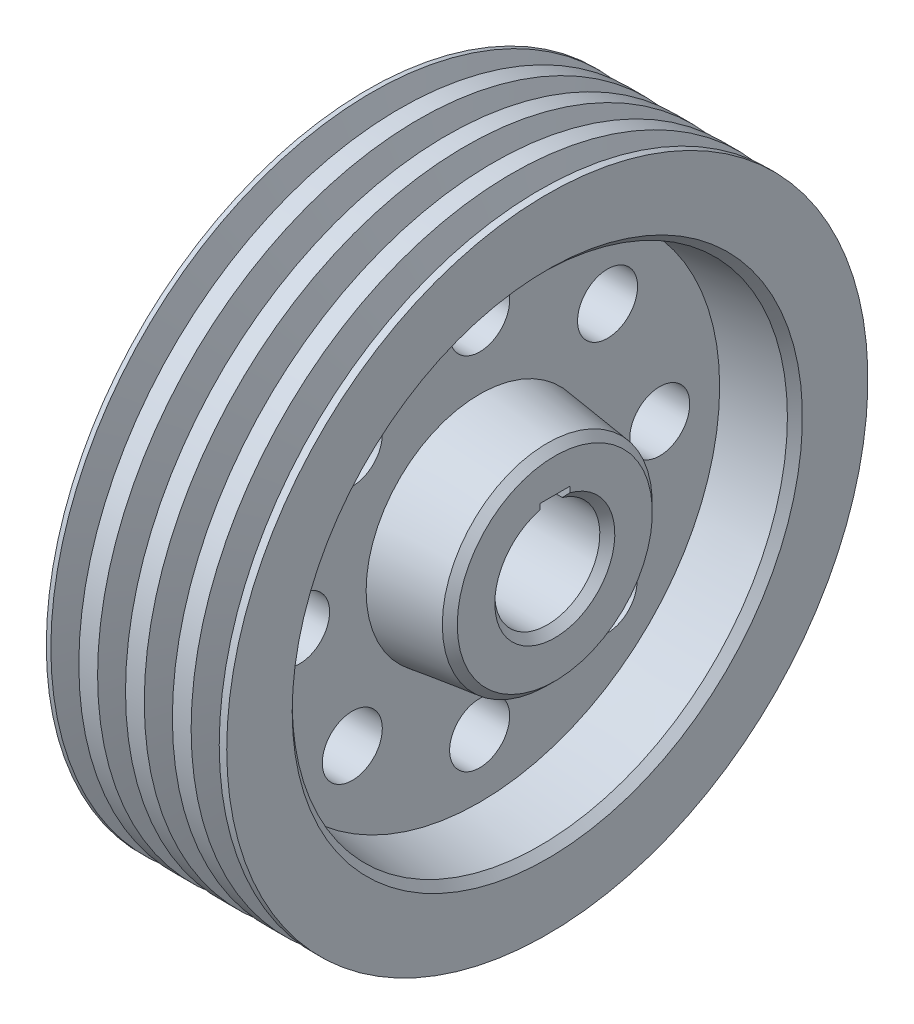
SolidWorks part; units mm, degrees
ref_plane "前视基准面" through (0, 0, 0) normal (0, 0, 1) x (1, 0, 0)
ref_plane "上视基准面" through (0, 0, 0) normal (0, 1, 0) x (1, 0, 0)
ref_plane "右视基准面" through (0, 0, 0) normal (1, 0, 0) x (0, 0, -1)
sketch "草图2" plane through (0, 0, 0) normal (0, 0, 1) x (1, 0, 0)
  line L0 (0, 0) -> (52, 0)
  line L3 (2, 14) -> (50, 14)
  line L4 (50, 68) -> (48, 66)
  line L5 (50, 27.9836) -> (31.9654, 30.2618)
  line L6 (52, 16) -> (52, 26)
  line L7 (0, 16) -> (2, 14)
  line L8 (50, 14) -> (52, 16)
  line L9 (5.9417, 77.6141) -> (3.2124, 85.5405)
  line L10 (2, 85.5405) -> (2, 68)
  line L11 (2, 85.5405) -> (3.2124, 85.5405)
  line L12 (52, 26) -> (50, 27.9836)
  line L14 (50, 68) -> (50, 85.45)
  line L15 (50, 85.45) -> (48, 85.45)
  line L16 (48, 85.45) -> (45.2863, 77.5688)
  line L17 (48, 66) -> (31.9654, 63.9744)
  line L18 (31.9654, 63.9744) -> (31.9654, 30.2618)
  line L19 (45.2863, 77.5688) -> (43.2863, 77.5688)
  line L20 (43.2863, 77.5688) -> (40.557, 85.4953)
  line L21 (40.557, 85.4953) -> (35.557, 85.4953)
  line L22 (35.557, 85.4953) -> (32.8433, 77.6141)
  line L23 (32.8433, 77.6141) -> (30.8433, 77.6141)
  line L24 (30.8433, 77.6141) -> (28.114, 85.5405)
  line L25 (28.114, 85.5405) -> (23.114, 85.5405)
  line L26 (23.114, 85.5405) -> (20.4003, 77.6594)
  line L27 (20.4003, 77.6594) -> (18.4003, 77.6141)
  line L28 (18.4003, 77.6141) -> (15.671, 85.5405)
  line L29 (15.671, 85.5405) -> (10.671, 85.5405)
  line L30 (10.671, 85.5405) -> (7.9417, 77.6141)
  line L31 (7.9417, 77.6141) -> (5.9417, 77.6141)
  line L32 (2, 68) -> (4, 66)
  line L34 (4, 66) -> (20, 63.9787)
  line L35 (20, 63.9787) -> (20, 30.2618)
  line L36 (20, 30.2618) -> (2, 27.9836)
  line L37 (2, 27.9836) -> (0, 26)
  line L38 (0, 26) -> (0, 16)
revolve "旋转1" add sketch "草图2" angle 360 about L0
sketch "草图3" plane through (31.9654, 0, 0) normal (1, 0, 0) x (0, 0, -1)
  circle A1 centre (34.0955, 34.0955) radius 8
  circle A2 centre (0, 48) radius 8
  circle A3 centre (-33.9411, 33.9411) radius 8
  circle A4 centre (-48, 0) radius 8
  circle A5 centre (0, -48) radius 8
  circle A6 centre (48, 0) radius 8
  circle A7 centre (33.9411, -33.9411) radius 8
  circle A8 centre (-33.9411, -33.9411) radius 8
extrude "切除-拉伸1" cut sketch "草图3" against normal through all both and the other way through all
sketch "草图4" plane through (0, 0, 0) normal (1, 0, 0) x (0, 0, -1)
  line L0 (-3.9952, 12.8736) -> (4.0048, 12.8736)
  line L2 (-3.9952, 12.8736) -> (-3.9952, 17)
  line L3 (-3.9952, 17) -> (4.0048, 17)
  line L4 (4.0048, 17) -> (4.0048, 12.8736)
extrude "切除-拉伸7" cut sketch "草图4" against normal blind 100 and the other way through all
